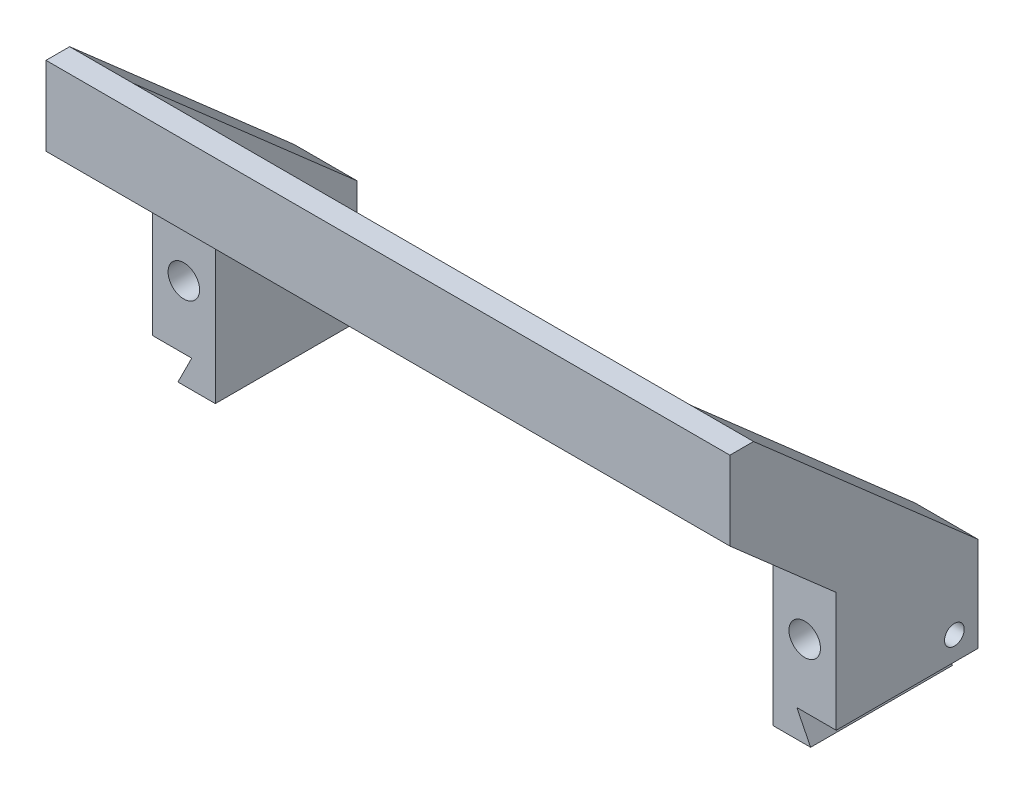
SolidWorks part; units mm, degrees
ref_plane "Front Plane" through (0, 0, 0) normal (0, 0, 1) x (1, 0, 0)
ref_plane "Top Plane" through (0, 0, 0) normal (0, 1, 0) x (1, 0, 0)
ref_plane "Right Plane" through (0, 0, 0) normal (1, 0, 0) x (0, 0, -1)
sketch "Sketch1" plane through (0, 0, 0) normal (1, 0, 0) x (0, 0, -1)
  line L0 (0, 0) -> (0, 16)
  line L2 (-18, 19.1579) -> (-18, 0)
  line L3 (-18, 0) -> (0, 0)
  line L4 (-18, 19.1579) -> (-31.5, 31)
  line L5 (-31.5, 31) -> (-31.5, 41)
  line L6 (-31.5, 41) -> (-28.5, 41)
  line L7 (-28.5, 41) -> (0, 16)
  dimension "D2" = 16
  dimension "D3" = 18
  dimension "D5" = 10.5
  dimension "D6" = 3
  dimension "D7" = 10
extrude "Boss-Extrude1" add sketch "Sketch1" along normal blind 8
sketch "Sketch2" plane through (8, 0, 0) normal (1, 0, 0) x (0, 0, -1)
  line L0 (-18, 19.1579) -> (-18, 0) construction
  line L1 (-18, 5) -> (0, 5)
  line L2 (-18, 5) -> (-18, 0)
  line L3 (-18, 0) -> (0, 0)
  line L4 (0, 5) -> (0, 0)
  line L5 (0, 0) -> (0, 16) construction
  dimension "D1" = 5
extrude "Cut-Extrude1" [suppressed] cut sketch "Sketch2" against normal blind 4
sketch "Sketch3" plane through (0, 0, 0) normal (0, 0, -1) x (-1, 0, 0)
  line L0 (-8, 0) -> (-5, 0)
  line L1 (-8, 0) -> (0, 0) construction
  line L2 (-5, 0) -> (-3, 4)
  line L3 (-3, 4) -> (-8, 4)
  line L4 (-8, 0) -> (-8, 16) construction
  line L5 (-8, 4) -> (-8, 0)
  dimension "D1" = 5
  dimension "D2" = 3
  dimension "D3" = 4
extrude "Cut-Extrude2" cut sketch "Sketch3" against normal through all
sketch "Sketch5" plane through (8, 0, 0) normal (1, 0, 0) x (0, 0, -1)
  line L0 (0, 4) -> (0, 16) construction
  line L1 (-18, 4) -> (0, 4) construction
  circle A0 centre (-3, 7) radius 1
  dimension "D1" = 2
  dimension "D3" = 3
  dimension "D2" = 3
hole_wizard "M3x0.5 Tapped Hole1" positions "3DSketch1" profile "Sketch6" tap size "M3x0.5" standard "ANSI Metric" end condition through all
sketch3d "3DSketch1"
  point P0 (8, 7, 3)
sketch "Sketch6" plane through (8, 7, 3) normal (0, 1, 0) x (0, 0, -1)
  line L0 (0, 0) -> (0, 86.83)
  line L1 (0, 86.83) -> (1.25, 86.83)
  line L2 (1.25, 86.83) -> (1.25, 0)
  line L5 (1.25, 0) -> (0, 0)
  line L11 (0, -6.35) -> (0, 107.95) construction
  dimension "Thread Major Dia." = 2.5
  dimension "Thru Tap Drill Depth" = 86.83
sketch "Sketch7" plane through (0, 0, 0) normal (-1, 0, 0) x (0, 0, 1)
  line L1 (28.5, 41) -> (31.5, 41)
  line L2 (28.5, 41) -> (28.5, 31)
  line L3 (28.5, 31) -> (31.5, 31)
  line L4 (31.5, 41) -> (31.5, 31)
extrude "Boss-Extrude2" add sketch "Sketch7" along normal blind 4
sketch "Sketch8" plane through (-4, 0, 0) normal (-1, 0, 0) x (0, 0, 1)
  line L0 (31.5, 31) -> (31.5, 41) construction
  line L1 (28.5, 41) -> (31.5, 41)
  line L2 (28.5, 41) -> (28.5, 31)
  line L3 (28.5, 31) -> (31.5, 31)
  line L4 (31.5, 41) -> (31.5, 31)
  dimension "D1" = 10
extrude "Boss-Extrude3" add sketch "Sketch8" along normal blind 66.83
ref_plane "Plane1" through (-35.415, 0, 0) normal (-1, 0, 0) x (0, 0, 1)
mirror "Mirror1" about plane through (-35.415, 0, 0) normal (-1, 0, 0) of "M3x0.5 Tapped Hole1", "Cut-Extrude2", "Boss-Extrude1"
sketch "Sketch9" plane through (-78.83, 0, 0) normal (-1, 0, 0) x (0, 0, 1)
  line L1 (28.5, 41) -> (31.5, 41)
  line L2 (28.5, 41) -> (28.5, 31)
  line L3 (28.5, 31) -> (31.5, 31)
  line L4 (31.5, 41) -> (31.5, 31)
extrude "Boss-Extrude4" [suppressed] add sketch "Sketch9" along normal blind 4
sketch "Sketch10" plane through (0, 0, 18) normal (0, 0, 1) x (1, 0, 0)
  line L1 (8, 19.1579) -> (8, 4) construction
  line L2 (3, 4) -> (8, 4) construction
  circle A0 centre (4, 12) radius 2
  dimension "D1" = 4
  dimension "D2" = 8
  dimension "D3" = 4
extrude "Cut-Extrude3" cut sketch "Sketch10" against normal through all
sketch "Sketch11" plane through (0, 0, 18) normal (0, 0, 1) x (1, 0, 0)
  line L1 (-78.83, 19.1579) -> (-78.83, 4) construction
  line L2 (-78.83, 4) -> (-73.83, 4) construction
  circle A0 centre (-74.83, 12) radius 2
  dimension "D1" = 4
  dimension "D2" = 8
  dimension "D3" = 4
extrude "Cut-Extrude4" cut sketch "Sketch11" against normal through all
sketch "Sketch12" plane through (0, 0, 0) normal (0, 0, -1) x (-1, 0, 0)
  line L1 (0, 0) -> (-8, 0)
  line L2 (0, 0) -> (0, 0.5)
  line L3 (0, 0.5) -> (-8, 0.5)
  line L4 (-8, 0) -> (-8, 0.5)
  dimension "D1" = 0.5
  dimension "D2" = 8
extrude "Cut-Extrude5" cut sketch "Sketch12" against normal through all
sketch "Sketch13" plane through (0, 0, 0) normal (0, 0, -1) x (-1, 0, 0)
  line L1 (70.83, 0) -> (78.83, 0)
  line L2 (70.83, 0) -> (70.83, 0.5)
  line L3 (70.83, 0.5) -> (78.83, 0.5)
  line L4 (78.83, 0) -> (78.83, 0.5)
  dimension "D1" = 8
  dimension "D2" = 0.5
extrude "Cut-Extrude6" cut sketch "Sketch13" against normal through all
